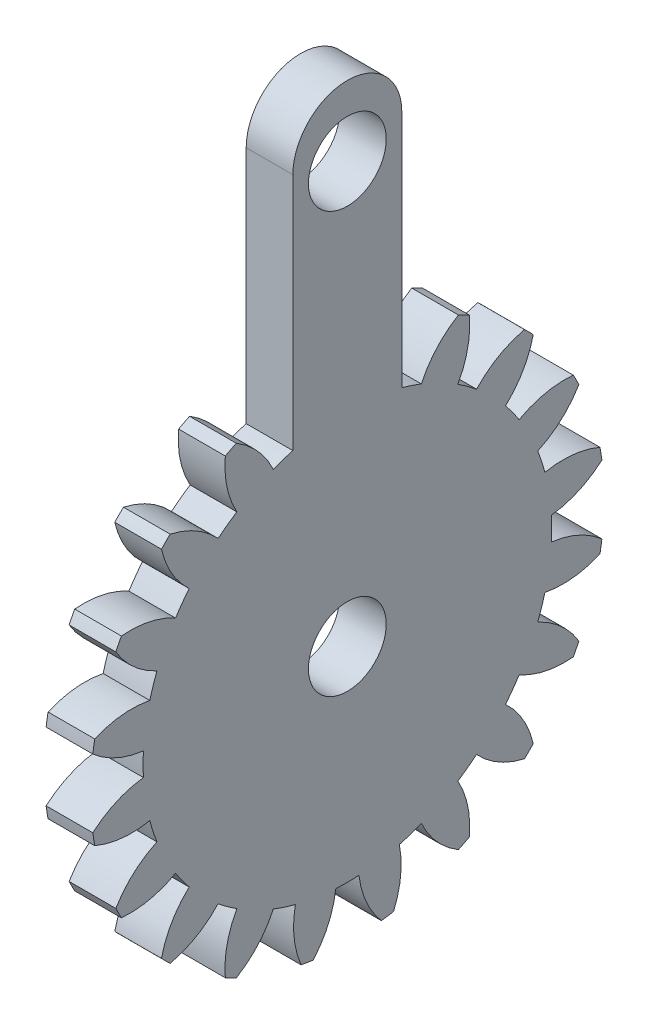
SolidWorks part; units mm, degrees
ref_plane "Plane1" through (0, 0, 0) normal (0, 0, 1) x (1, 0, 0)
ref_plane "Plane2" through (0, 0, 0) normal (0, 1, 0) x (1, 0, 0)
ref_plane "Plane3" through (0, 0, 0) normal (1, 0, 0) x (0, 0, -1)
sketch "HoldingSke" plane through (0, 0, 0) normal (0, 1, 0) x (1, 0, 0)
  line L0 (0, 0) -> (0.6265, -0.228)
  line L1 (-15, 0) -> (100, 0) construction
  line L2 (0, 0) -> (-2.1039, 2.3779)
  line L3 (0, 0) -> (-11.863, 4.5341)
  line L4 (0, 0) -> (8.1152, 2.9537)
  line L5 (0, 0) -> (-46.8476, -17.4728)
  line L6 (0, 0) -> (-2.4869, -1.6779)
  line L7 (-2.1039, 2.3779) -> (8.6586, 51.2059)
  line L8 (-76.2, 54.61) -> (-75.3, 54.61)
  line L9 (-71.009, 38.7566) -> (-53.1078, 45.2721)
  line L10 (-76.2, 71.12) -> (104.1128, 71.12)
  line L11 (0, 0) -> (-3, 0)
  line L12 (-76.2, 101.6) -> (-76.147, 101.6)
  line L13 (24.9733, 27.94) -> (52.9518, 28.4284)
  line L14 (24.9733, 27.94) -> (24.9743, 27.94)
  line L15 (24.9733, 27.94) -> (100.4006, 29.5858)
  line L16 (-63.627, -1.5) -> (-12.827, -1.5)
  circle A0 centre (0, 0) radius 2.5
  circle A1 centre (0, 0) radius 13.124
  circle A2 centre (0, 0) radius 37.5
  circle A3 centre (0, 0) radius 2.5
  dimension "MHD" = 26.248
  dimension "Hub_dia" = 75
  dimension "Bore" = 5
  dimension "MBD" = 5
  dimension "Num_teeth" = 20
  dimension "Pitch" = 0.6667
  dimension "Overall_len" = 50
  dimension "Show_teeth" = 20
  dimension "Thickness" = 3
  dimension "OAL" = 50.0001
  dimension "T_dim" = 0.9
  dimension "Ap" = 20
  dimension "H" = 19.05
  dimension "Pitch_radius" = 180.3128
  dimension "Width" = 3
  dimension "Backlash" = 0.053
  dimension "Addendum_fac" = 1
  dimension "Dedendum_fac" = 1.25
  dimension "Clearance_fac" = 0.25
  dimension "Dedendum_add" = 0.001
  dimension "Module" = 1.5
sketch "BasProSke" plane through (0, 0, 0) normal (0, 1, 0) x (1, 0, 0)
  line L0 (-10, 0) -> (60, 0) construction
  line L1 (0, 0) -> (0, 16.5)
  line L2 (0, 0) -> (3, 0)
  line L3 (3, 0) -> (3, 16.5)
  line L4 (3, 16.5) -> (0, 16.5)
  dimension "Thickness" = 3
  dimension "Diameter" = 33
revolve "Base-Revolve" add sketch "BasProSke" angle 360 about L0
sketch "TooCutSke" plane through (0, 0, 0) normal (1, 0, 0) x (0, 0, -1)
  line L1 (0, 0) -> (0, 107) construction
  line L2 (0, 0) -> (-1.2696, 14.9462) construction
  line L3 (0, 0) -> (-4.6808, 29.5532) construction
  line L4 (-1.2696, 14.9462) -> (-2.3404, 14.7766) construction
  arc A0 (0.7438, 13.1029) -> (-0.7438, 13.1029) centre (0, 0) ccw
  arc A1 (2.21, 16.377) -> (-2.21, 16.377) centre (0, 0) ccw
  circle A2 centre (0, 0) radius 15 construction
  circle A3 centre (0, 0) radius 14.0954 construction
  arc A4 (-0.7438, 13.1029) -> (-2.21, 16.377) centre (-6.7025, 12.3999) ccw
  arc A5 (2.21, 16.377) -> (0.7438, 13.1029) centre (6.7025, 12.3999) ccw
  point P11 (0, 0)
  dimension "Root_dia" = 26.248
  dimension "Overcut_dia" = 33.0508
  dimension "Pitch_dia" = 30
  dimension "Base_dia" = 28.1908
  dimension "Flank_rad" = 6
  dimension "Half_ang" = 9
  dimension "Half_CT" = 1.0841
extrude "ToothCut" cut sketch "TooCutSke" along normal through all
fillet "Breaks" [suppressed] radius 0.03
fillet "RootFillets" [suppressed] radius 0.376
pattern_circular "TeethCuts" count 20 every 18 about axis through (-10, 0, 0) along (1, 0, 0) of "ToothCut", "RootFillets", "Breaks"
sketch "HubNeaOneSke" plane through (0, 0, 0) normal (-1, 0, 0) x (0, 0, 1)
  circle A0 centre (0, 0) radius 13.124
  dimension "Diameter" = 26.248
extrude "HubNearOne" [suppressed] add sketch "HubNeaOneSke" along normal blind 47.0001
sketch "HubNeaBotSke" plane through (0, 0, 0) normal (-1, 0, 0) x (0, 0, 1)
  circle A0 centre (0, 0) radius 13.124
  dimension "Diameter" = 26.248
extrude "HubNearBoth" [suppressed] add sketch "HubNeaBotSke" along normal blind 23.5
ref_plane "FarPln" through (3, 0, 0) normal (1, 0, 0) x (0, 0, -1)
sketch "HubFarSke" plane through (3, 0, 0) normal (1, 0, 0) x (0, 0, -1)
  circle A0 centre (0, 0) radius 13.124
  dimension "Diameter" = 26.248
extrude "HubFar" [suppressed] add sketch "HubFarSke" along normal blind 23.5
sketch "BorSke" plane through (0, 0, 0) normal (1, 0, 0) x (0, 0, -1)
  circle A0 centre (0, 0) radius 2.5
  dimension "Diameter" = 5
extrude "Bore" [suppressed] cut sketch "BorSke" along normal mid plane 100.0001
sketch "KeySke" plane through (0, 0, 0) normal (1, 0, 0) x (0, 0, -1)
  line L0 (-1, 0) -> (-1, 3.4)
  line L1 (-1, 3.4) -> (1, 3.4)
  line L2 (1, 3.4) -> (1, 0)
  line L3 (0, 0) -> (0, 34) construction
  line L4 (-1, 0) -> (1, 0)
  dimension "Offset" = 3.4
  dimension "Width" = 2
extrude "Keyway" [suppressed] cut sketch "KeySke" along normal mid plane 100.0001
pattern_circular "Keyway2" [suppressed] count 2 every 90 about axis through (-10, 0, 0) along (1, 0, 0)
sketch "草图2" plane through (0, 0, 0) normal (-1, 0, 0) x (0, 0, 1)
  line L0 (0, 0) -> (0, 28) construction
  line L1 (0, 0) -> (0, 107) construction
  line L2 (-3.5, 0) -> (-3.5, 28)
  line L3 (3.5, 0) -> (3.5, 28)
  arc A0 (-3.5, 0) -> (3.5, 0) centre (0, 0) ccw
  arc A1 (3.5, 28) -> (-3.5, 28) centre (0, 28) ccw
  point P5 (0, 14)
  dimension "D1" = 3.5
  dimension "D2" = 28
extrude "凸台-拉伸3" add sketch "草图2" against normal up to surface (3 mm away) up to face at (3, 0, 0)
sketch "草图3" plane through (0, 0, 0) normal (-1, 0, 0) x (0, 0, 1)
  line L0 (0, 0) -> (0, 107) construction
  circle A0 centre (0, 0) radius 2.5
  circle A1 centre (0, 27) radius 2.5
  point P7 (0, 0)
  point P8 (0, 0)
  dimension "D1" = 27
  dimension "D2" = 5
  dimension "D3" = 5
extrude "切除-拉伸2" cut sketch "草图3" against normal through all
equation "' \"Module@HoldingSke\" = 6.35"
equation "' \"Num_teeth@HoldingSke\" = 12"
equation "' \"Ap@HoldingSke\" =  20"
equation "' \"Ap@HoldingSke\" = 20"
equation "' \"Width@HoldingSke\" = 0.5 * 25.4"
equation "' \"Hub_dia@HoldingSke\"= 1 * 25.4"
equation "' \"Hub_dia@HoldingSke\" = 1 * 25.4"
equation "' \"Overall_len@HoldingSke\" = 1.0 * 25.4"
equation "' \"Bore@HoldingSke\" = 0.75 * 25.4"
equation "' \"T_dim@HoldingSke\" = 0.1 * 25.4"
equation "' \"Width@KeySke\" = 0.25 * 25.4"
equation "' \"Show_teeth@HoldingSke\" = 13"
equation "' \"Backlash@HoldingSke\" = 0.009 * 25.4"
equation "' \"Addendum_fac@HoldingSke\" = 1.0"
equation "' \"Dedendum_fac@HoldingSke\" = 1.25"
equation "' \"Dedendum_add@HoldingSke\" = 0.00005 * 25.4"
equation "' \"Clearance_fac@HoldingSke\" = 0.25"
equation "\"Pitch@HoldingSke\" = 1 / \"Module@HoldingSke\""
equation "\"Overcut_dia@TooCutSke\" = (\"Num_teeth@HoldingSke\" + 2 * \"Addendum_fac@HoldingSke\") / \"Pitch@HoldingSke\" + 0.002 * 25.4"
equation "\"Pitch_dia@TooCutSke\" = \"Num_teeth@HoldingSke\" / \"Pitch@HoldingSke\""
equation "\"Base_dia@TooCutSke\" = \"Num_teeth@HoldingSke\" / \"Pitch@HoldingSke\" * cos((\"Ap@HoldingSke\"  * 3.14159265 / 180))"
equation "\"Root_dia@TooCutSke\" = (\"Num_teeth@HoldingSke\" + 2) / \"Pitch@HoldingSke\" - 2 * (\"Addendum_fac@HoldingSke\" + \"Dedendum_fac@HoldingSke\") / \"Pitch@HoldingSke\" - \"Dedendum_add@HoldingSke\" * 2"
equation "\"Half_ang@TooCutSke\" = 180 / \"Num_teeth@HoldingSke\""
equation "\"Half_CT@TooCutSke\" = \"Num_teeth@HoldingSke\" / \"Pitch@HoldingSke\" * sin((3.14159265 / 2 / \"Num_teeth@HoldingSke\")) / 2 - 7 * \"Backlash@HoldingSke\" / 4"
equation "\"Flank_rad@TooCutSke\" = \"Num_teeth@HoldingSke\" / \"Pitch@HoldingSke\" / 5"
equation "\"Radius@RootFillets\" = \"Clearance_fac@HoldingSke\" / \"Pitch@HoldingSke\" + \"Dedendum_add@HoldingSke\""
equation "\"Break_rad@Breaks\" = 0.02 / \"Pitch@HoldingSke\""
equation "\"Thickness@HoldingSke\" = \"Width@HoldingSke\""
equation "\"OAL@HoldingSke\" = \"Thickness@HoldingSke\""
equation "\"MHD@HoldingSke\" = (\"Num_teeth@HoldingSke\" + 2) / \"Pitch@HoldingSke\" - 2 * (\"Addendum_fac@HoldingSke\" + \"Dedendum_fac@HoldingSke\")  / \"Pitch@HoldingSke\" - \"Dedendum_add@HoldingSke\" * 2"
equation "\"MBD@HoldingSke\" = (\"Num_teeth@HoldingSke\" + 2) / \"Pitch@HoldingSke\" - 2 * (\"Addendum_fac@HoldingSke\" + \"Dedendum_fac@HoldingSke\")  / \"Pitch@HoldingSke\" - \"Dedendum_add@HoldingSke\" * 2 - 0.002 * 25.4"
equation "\"MHD@HoldingSke\" = ((sgn( \"MHD@HoldingSke\" - \"Hub_dia@HoldingSke\" )-1)*( \"MHD@HoldingSke\" - \"Hub_dia@HoldingSke\" ))/-2+ \"Hub_dia@HoldingSke\""
equation "\"MBD@HoldingSke\" = ((sgn( \"MBD@HoldingSke\" - \"Bore@HoldingSke\" )-1)*( \"MBD@HoldingSke\" - \"Bore@HoldingSke\" ))/-2+ \"Bore@HoldingSke\""
equation "\"OAL@HoldingSke\" = ((sgn( \"OAL@HoldingSke\" - \"Overall_len@HoldingSke\" )+1)*( \"OAL@HoldingSke\" - \"Overall_len@HoldingSke\" ))/2 + \"Overall_len@HoldingSke\" + 0.000002 * 25.4"
equation "\"Num_teeth@TeethCuts\" = int( \"Show_teeth@HoldingSke\" ) + 1"
equation "\"Num_teeth@TeethCuts\" = ((sgn( \"Num_teeth@TeethCuts\" - \"Num_teeth@HoldingSke\" )-1)*( \"Num_teeth@TeethCuts\" - \"Num_teeth@HoldingSke\" ))/-2+ \"Num_teeth@HoldingSke\""
equation "\"Num_teeth@TeethCuts\" = ((sgn( \"Num_teeth@TeethCuts\" - 2.0)+1)*( \"Num_teeth@TeethCuts\" - 2.0))/2 +2.0"
equation "\"Angle@TeethCuts\" = 360.0 / \"Num_teeth@HoldingSke\""
equation "\"Diameter@BasProSke\" = (\"Num_teeth@HoldingSke\" + 2 * \"Addendum_fac@HoldingSke\") / \"Pitch@HoldingSke\""
equation "\"Thickness@BasProSke\"  = \"Thickness@HoldingSke\""
equation "' \"Fillet_rad@BasProSke\" =  \"Thickness@HoldingSke\" * 0.05"
equation "' \"Fillet_rad@BasProSke\" = \"Thickness@HoldingSke\" * 0.05"
equation "\"MHD@HoldingSke\" = ((sgn( \"MHD@HoldingSke\" - \"Root_dia@TooCutSke\" )-1)*( \"MHD@HoldingSke\" - \"Root_dia@TooCutSke\" ))/-2+ \"Root_dia@TooCutSke\""
equation "\"Diameter@HubNeaOneSke\" = \"MHD@HoldingSke\""
equation "\"Length@HubNearOne\" = \"OAL@HoldingSke\" - \"Thickness@BasProSke\""
equation "\"Diameter@HubNeaBotSke\" = \"MHD@HoldingSke\""
equation "\"Length@HubNearBoth\" = ( \"OAL@HoldingSke\" - \"Thickness@BasProSke\" ) / 2.0"
equation "\"Thickness@FarPln\" = \"Thickness@BasProSke\""
equation "\"Diameter@HubFarSke\" = \"MHD@HoldingSke\""
equation "\"Length@HubFar\" = ( \"OAL@HoldingSke\" - \"Thickness@BasProSke\" ) / 2.0"
equation "\"Diameter@BorSke\" = \"MBD@HoldingSke\""
equation "\"D1@Bore\" = \"OAL@HoldingSke\" * 2.0"
equation "\"D1@Keyway\" = \"OAL@HoldingSke\" * 2.0"
equation "\"Offset@KeySke\" = \"T_dim@HoldingSke\" + \"MBD@HoldingSke\" / 2.0"
